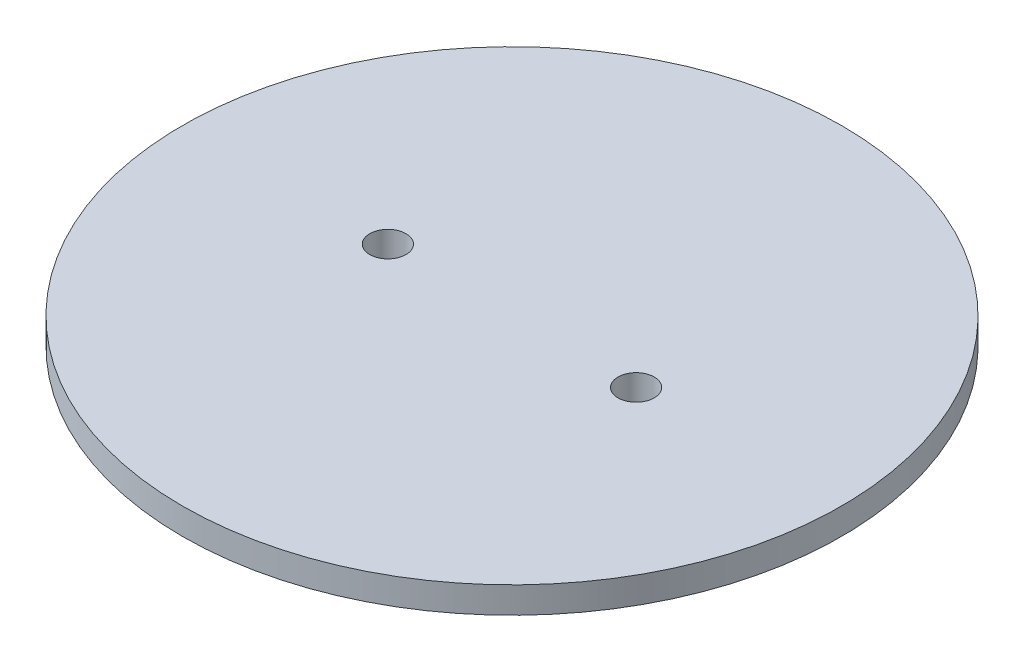
SolidWorks part; units mm, degrees
ref_plane "前基準面" through (0, 0, 0) normal (0, 0, 1) x (1, 0, 0)
ref_plane "上基準面" through (0, 0, 0) normal (0, 1, 0) x (1, 0, 0)
ref_plane "右基準面" through (0, 0, 0) normal (1, 0, 0) x (0, 0, -1)
sketch "草圖1" plane through (0, 0, 0) normal (0, 1, 0) x (1, 0, 0)
  line L0 (-18.83, 0) -> (18.83, 0)
  line L1 (-55, 0) -> (55, 0) construction
  line L2 (0, -55) -> (0, 55) construction
  circle A0 centre (0, 0) radius 50
  circle A1 centre (-18.83, 0) radius 2.75
  circle A2 centre (18.83, 0) radius 2.75
  dimension "D1" = 100
  dimension "D4" = 5.5
  dimension "D5" = 5.5
  dimension "D2" = 37.66
  dimension "D3" = 18.83
extrude "填料-伸長1" add sketch "草圖1" along normal blind 4
